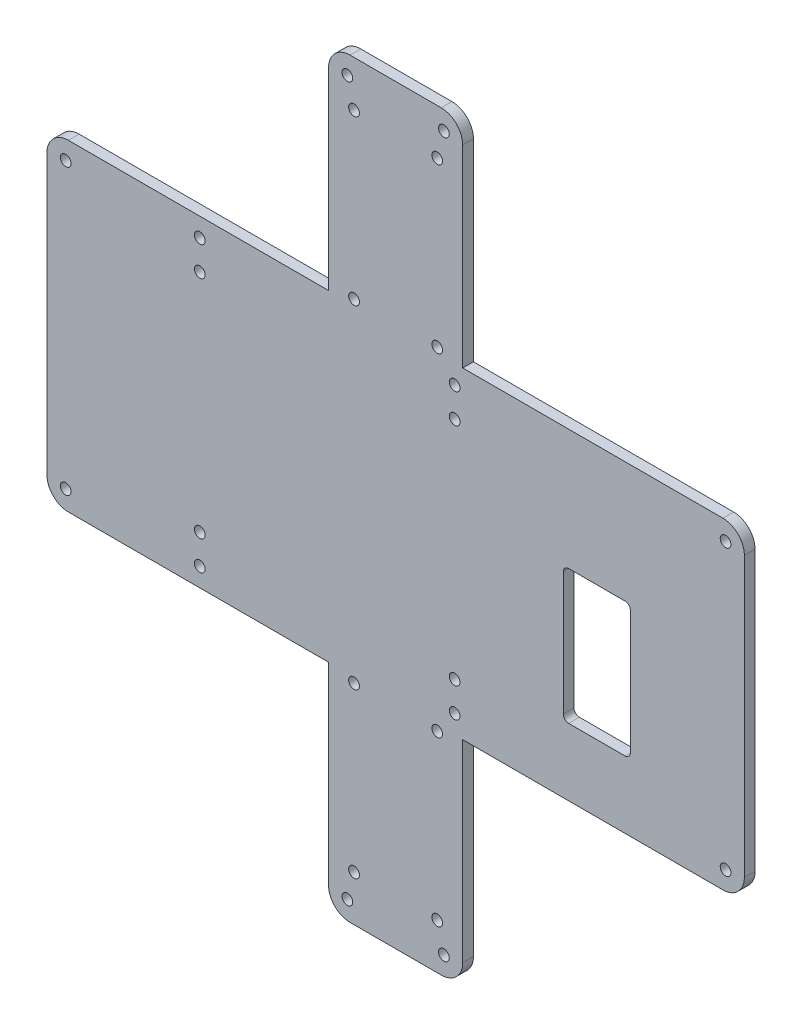
SolidWorks part; units mm, degrees
ref_plane "前视基准面" through (0, 0, 0) normal (0, 0, 1) x (1, 0, 0)
ref_plane "上视基准面" through (0, 0, 0) normal (0, 1, 0) x (1, 0, 0)
ref_plane "右视基准面" through (0, 0, 0) normal (1, 0, 0) x (0, 0, -1)
sketch "草图2" plane through (0, 0, 0) normal (0, 0, 1) x (1, 0, 0)
  line L1 (-144.4721, 149.2876) -> (115.5279, 149.2876)
  line L2 (-144.4721, 149.2876) -> (-144.4721, -130.7124)
  line L3 (-144.4721, -130.7124) -> (115.5279, -130.7124)
  line L4 (115.5279, 149.2876) -> (115.5279, -130.7124)
  line L5 (-94.4721, 149.2876) -> (65.5279, 149.2876)
  line L6 (-94.4721, 149.2876) -> (-94.4721, 69.2876)
  line L7 (-94.4721, -130.7124) -> (65.5279, -130.7124)
  line L8 (65.5279, 149.2876) -> (65.5279, 69.2876)
  line L9 (-144.4721, -50.7124) -> (-94.4721, -50.7124)
  line L10 (-144.4721, -50.7124) -> (-144.4721, 69.2876)
  line L11 (-144.4721, 69.2876) -> (-94.4721, 69.2876)
  line L12 (115.5279, -50.7124) -> (115.5279, 69.2876)
  line L28 (-94.4721, -50.7124) -> (-94.4721, -130.7124)
  line L29 (65.5279, 69.2876) -> (115.5279, 69.2876)
  line L30 (65.5279, -50.7124) -> (65.5279, -130.7124)
  line L31 (65.5279, -50.7124) -> (115.5279, -50.7124)
  line L36 (-144.4721, 9.2876) -> (115.5279, 9.2876)
  line L38 (-87.4721, 51.2876) -> (7.5279, 51.2876)
  line L39 (-87.4721, 51.2876) -> (-87.4721, -43.7124)
  line L40 (-87.4721, -43.7124) -> (7.5279, -43.7124)
  line L41 (7.5279, 51.2876) -> (7.5279, -43.7124)
  line L42 (-87.4721, -32.7124) -> (7.5279, -32.7124)
  line L43 (-87.4721, -32.7124) -> (-87.4721, 62.2876)
  line L44 (-87.4721, 62.2876) -> (7.5279, 62.2876)
  line L49 (7.5279, -32.7124) -> (7.5279, 62.2876)
  line L50 (-29.9721, 132.2876) -> (1.0279, 132.2876)
  line L51 (-29.9721, 132.2876) -> (-29.9721, 71.2876)
  line L52 (-29.9721, 71.2876) -> (1.0279, 71.2876)
  line L57 (1.0279, 132.2876) -> (1.0279, 71.2876)
  line L59 (48.0279, 24.2876) -> (73.0279, 24.2876)
  line L60 (48.0279, 24.2876) -> (48.0279, -25.7124)
  line L61 (48.0279, -25.7124) -> (73.0279, -25.7124)
  line L62 (73.0279, 24.2876) -> (73.0279, -25.7124)
  line L75 (-94.4721, 69.2876) -> (65.5279, 69.2876)
  line L76 (-39.4721, 149.2876) -> (10.5279, 149.2876)
  line L77 (-39.4721, 149.2876) -> (-39.4721, -130.7124)
  line L78 (-39.4721, -130.7124) -> (10.5279, -130.7124)
  line L79 (10.5279, 149.2876) -> (10.5279, -130.7124)
  line L80 (-94.4721, -50.7124) -> (65.5279, -50.7124)
  circle A0 centre (60.5279, 9.2876) radius 45
  circle A33 centre (-137.4721, 62.2876) radius 2
  circle A34 centre (-137.4721, -43.7124) radius 2
  circle A35 centre (108.5279, -43.7124) radius 2
  circle A36 centre (108.5279, 62.2876) radius 2
  circle A37 centre (-32.4721, -123.7124) radius 2
  circle A38 centre (3.5279, -123.7124) radius 2
  circle A39 centre (-32.4721, 142.2876) radius 2
  circle A40 centre (3.5279, 142.2876) radius 2
  circle A41 centre (-87.4721, 51.2876) radius 2
  circle A42 centre (-87.4721, -43.7124) radius 2
  circle A43 centre (7.5279, -43.7124) radius 2
  circle A44 centre (7.5279, 51.2876) radius 2
  circle A45 centre (-87.4721, 62.2876) radius 2
  circle A46 centre (7.5279, 62.2876) radius 2
  circle A47 centre (-87.4721, -32.7124) radius 2
  circle A48 centre (7.5279, -32.7124) radius 2
  circle A49 centre (-29.9721, 132.2876) radius 2
  circle A50 centre (1.0279, 132.2876) radius 2
  circle A51 centre (-29.9721, 71.2876) radius 2
  circle A52 centre (1.0279, 71.2876) radius 2
  circle A53 centre (1.0279, -52.7124) radius 2
  circle A54 centre (-29.9721, -52.7124) radius 2
  circle A55 centre (1.0279, -113.7124) radius 2
  circle A56 centre (-29.9721, -113.7124) radius 2
  point P34 (115.5279, 9.2876)
  point P39 (-14.4721, 132.2876)
  point P40 (-14.4721, 149.2876)
  point P68 (-32.3659, 9.2876)
  point P78 (60.5279, 24.2876)
  dimension "D14" = 61
  dimension "D11" = 31
  dimension "D1" = 160
  dimension "D2" = 120
  dimension "D3" = 50
  dimension "D4" = 80
  dimension "D5" = 280
  dimension "D6" = 55
  dimension "D7" = 95
  dimension "D8" = 18
  dimension "D9" = 95
  dimension "D10" = 95
  dimension "D12" = 18
  dimension "D13" = 7
  dimension "D15" = 2
  dimension "D24" = 25
  dimension "D25" = 50
  dimension "D26" = 15
  dimension "D27" = 50
  dimension "D28" = 7
  dimension "D29" = 7
  dimension "D30" = 7
  dimension "D31" = 7
  dimension "D32" = 105
  dimension "D33" = 7
  dimension "D34" = 7
  dimension "D35" = 7
  dimension "D36" = 7
  dimension "D37" = 7
  dimension "D38" = 7
  dimension "D39" = 7
  dimension "D40" = 7
  dimension "D41" = 7
  dimension "D42" = 7
  dimension "D43" = 7
  dimension "D44" = 7
extrude "凸台-拉伸1" add sketch "草图2" along normal blind 4 contours A45 L44 L77 L75 L11 L2 L36 L43 A41 A33 | A47 L39 L36 L10 L9 L80 L77 L40 A42 A34 | A47 L42 L77 L36 L39 | A41 L43 L36 L77 L38 | A45 L43 A41 L38 L77 L44 | A47 L39 A42 L40 L77 L42 | A48 L41 L36 L77 L42 | A48 L41 A43 L40 L77 L80 L79 L36 | A46 L49 A44 L36 L79 L75 L77 L44 | A46 L44 L77 L38 A44 L49 | A44 L38 L77 L36 L49 | A48 L42 L77 L40 A43 L41 | A0 L36 L4 L29 L75 L79 A36 | A0 L36 L79 L80 L31 L12 A35 | L36 A0 L60 L59 L62 | L36 A0 L62 L61 L60 | L80 A54 L77 L7 L79 A53 A55 A38 A37 A56 | A52 L52 A51 L75 | A52 L75 L79 L5 L77 A51 L51 A49 L50 A50 L57 A40 A39 | A52 L57 A50 L50 A49 L51 A51 L52
fillet "圆角1" radius 8 8 edges at (10.5279, -130.7124, 2) (-39.4721, -130.7124, 2) (-144.4721, -50.7124, 2) (-144.4721, 69.2876, 2) (-39.4721, 149.2876, 2) (10.5279, 149.2876, 2) (115.5279, 69.2876, 2) (115.5279, -50.7124, 2)
fillet "圆角2" radius 2 4 edges at (48.0279, -25.7124, 2) (73.0279, -25.7124, 2) (48.0279, 24.2876, 2) (73.0279, 24.2876, 2)
